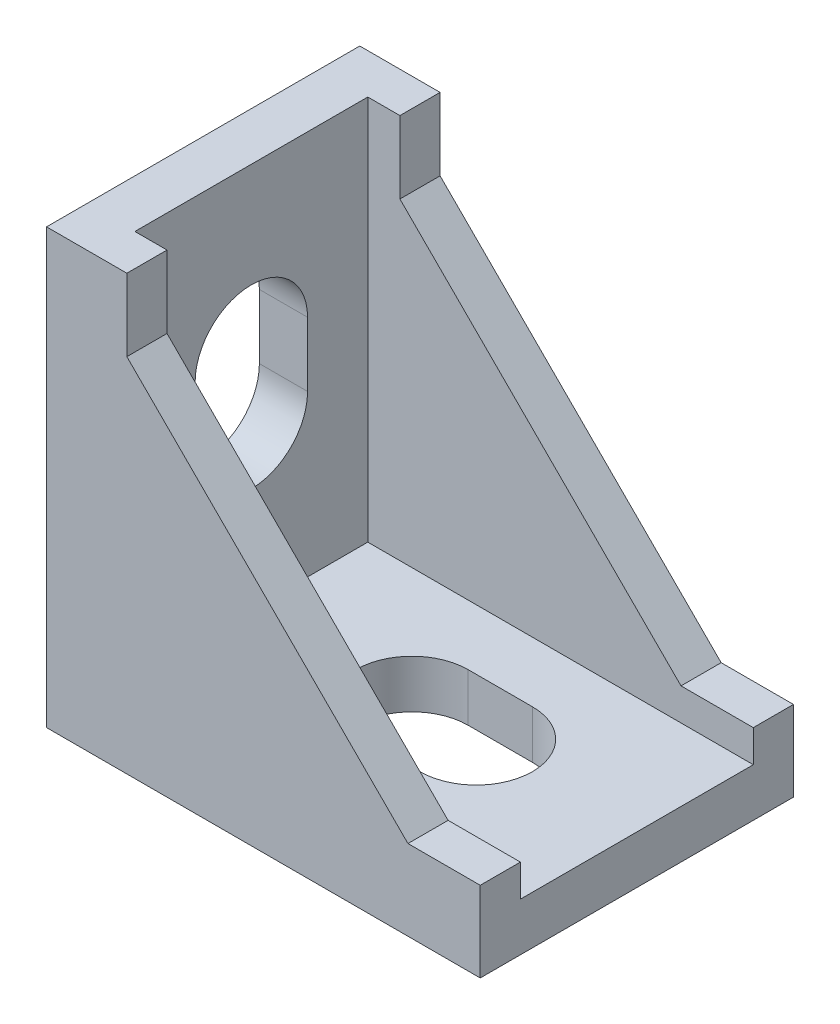
SolidWorks part; units mm, degrees
ref_plane "Front Plane" through (0, 0, 0) normal (0, 0, 1) x (1, 0, 0)
ref_plane "Top Plane" through (0, 0, 0) normal (0, 1, 0) x (1, 0, 0)
ref_plane "Right Plane" through (0, 0, 0) normal (1, 0, 0) x (0, 0, -1)
sketch "Sketch1" plane through (0, 0, 0) normal (0, 0, 1) x (1, 0, 0)
  line L0 (0, 0) -> (0, 27)
  line L1 (0, 27) -> (5, 27)
  line L2 (5, 27) -> (5, 22.5)
  line L3 (5, 22.5) -> (22.5, 5)
  line L4 (22.5, 5) -> (27, 5)
  line L5 (27, 5) -> (27, 0)
  line L6 (27, 0) -> (0, 0)
  dimension "D1" = 27
  dimension "D2" = 27
  dimension "D3" = 5
  dimension "D4" = 5
  dimension "D5" = 4.5
  dimension "D6" = 4.5
extrude "Boss-Extrude1" add sketch "Sketch1" along normal blind 19.5
ref_plane "Plane1" through (0, 0, 17) normal (0, 0, 1) x (1, 0, 0)
sketch "Sketch2" plane through (0, 0, 17) normal (0, 0, 1) x (1, 0, 0)
  line L2 (5, 27) -> (0, 27) construction
  line L5 (3, 27) -> (5, 27)
  line L6 (5, 27) -> (5, 22.5)
  line L7 (5, 22.5) -> (22.5, 5)
  line L8 (22.5, 5) -> (27, 5)
  line L11 (3, 27) -> (3, 3)
  line L12 (3, 3) -> (27, 3)
  line L13 (27, 0) -> (27, 5) construction
  line L14 (27, 3) -> (27, 5)
  line L15 (0, 27) -> (0, 0) construction
  line L16 (0, 0) -> (27, 0) construction
  dimension "D1" = 3
  dimension "D2" = 3
extrude "Cut-Extrude2" cut sketch "Sketch2" against normal blind 14.5
sketch "Sketch3" plane through (0, 3, 0) normal (0, 1, 0) x (1, 0, 0)
  line L0 (15, -2.5) -> (15, -17) construction
  line L1 (3, -2.5) -> (27, -2.5) construction
  line L2 (-14.85, -17) -> (14.85, -17) construction
  line L3 (3, -9.75) -> (27, -9.75) construction
  line L4 (3, -2.5) -> (3, -17) construction
  line L5 (27, -2.5) -> (27, -17) construction
  line L6 (13, -9.75) -> (17, -9.75) construction
  line L7 (13, -6.25) -> (17, -6.25)
  line L8 (13, -13.25) -> (17, -13.25)
  line L9 (3, -2.5) -> (3, -17) construction
  arc A0 (13, -6.25) -> (13, -13.25) centre (13, -9.75) ccw
  arc A1 (17, -13.25) -> (17, -6.25) centre (17, -9.75) ccw
  point P14 (15, -9.75)
  point P19 (9.5, -9.75)
  point P20 (20.5, -9.75)
  point P24 (15, -9.75)
  dimension "D2" = 11
  dimension "D1" = 7
extrude "Cut-Extrude3" cut sketch "Sketch3" against normal through all
sketch "Sketch4" plane through (3, 0, 0) normal (1, 0, 0) x (0, 0, -1)
  line L0 (-9.75, 3) -> (-9.75, 27) construction
  line L1 (-2.5, 3) -> (-17, 3) construction
  line L2 (-2.5, 27) -> (-17, 27) construction
  line L3 (-2.5, 15) -> (-17, 15) construction
  line L4 (-2.5, 27) -> (-2.5, 3) construction
  line L5 (-17, 14.85) -> (-17, -14.85) construction
  line L6 (-9.75, 13) -> (-9.75, 17) construction
  line L7 (-13.25, 13) -> (-13.25, 17)
  line L8 (-6.25, 13) -> (-6.25, 17)
  arc A0 (-13.25, 13) -> (-6.25, 13) centre (-9.75, 13) ccw
  arc A1 (-6.25, 17) -> (-13.25, 17) centre (-9.75, 17) ccw
  point P14 (-9.75, 15)
  point P19 (-9.75, 9.5)
  point P20 (-9.75, 20.5)
  dimension "D1" = 7
  dimension "D2" = 11
extrude "Cut-Extrude4" cut sketch "Sketch4" against normal through all
equation "\"19.5.00mm\"=195"
